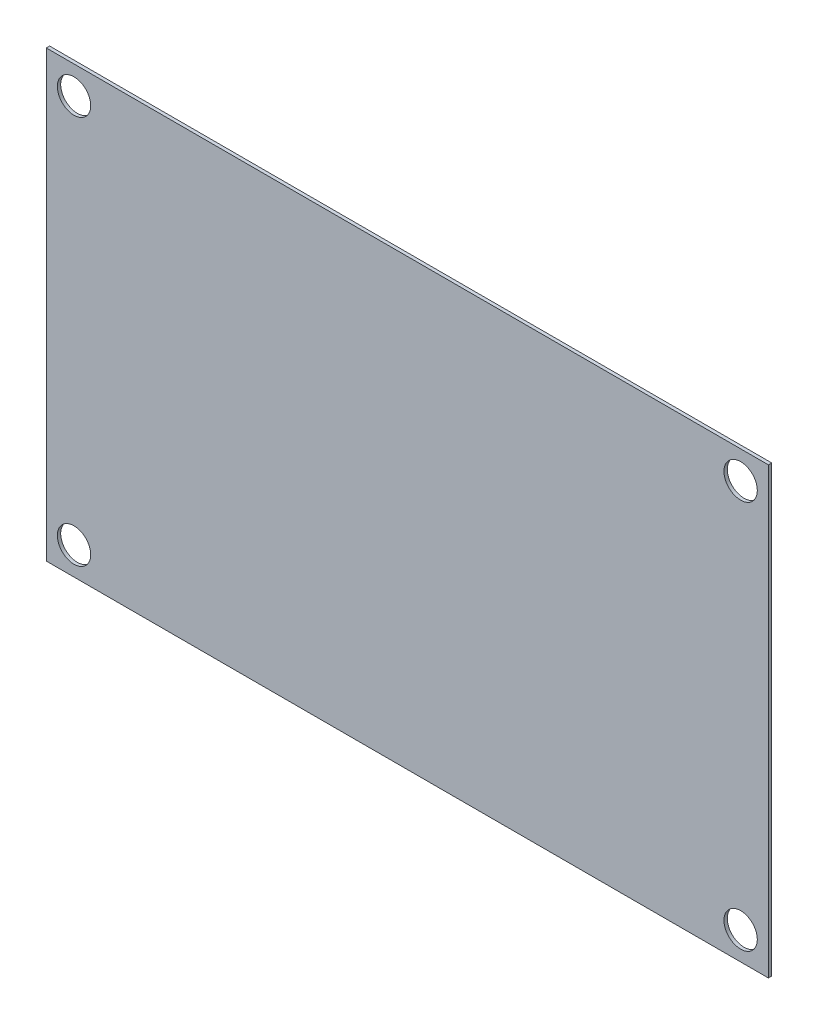
SolidWorks part; units mm, degrees
material "Copper"
ref_plane "Front Plane" through (0, 0, 0) normal (0, 0, 1) x (1, 0, 0)
ref_plane "Top Plane" through (0, 0, 0) normal (0, 1, 0) x (1, 0, 0)
ref_plane "Right Plane" through (0, 0, 0) normal (1, 0, 0) x (0, 0, -1)
sketch "Sketch1" plane through (0, 0, 0) normal (0, 0, 1) x (1, 0, 0)
  line L0 (-32.5, 17.5) -> (-30, 17.5) construction
  line L1 (-32.5, 20) -> (32.5, 20)
  line L2 (-32.5, 20) -> (-32.5, -20)
  line L3 (-32.5, -20) -> (32.5, -20)
  line L4 (32.5, 20) -> (32.5, -20)
  line L5 (-32.5, 20) -> (32.5, -20) construction
  line L6 (-32.5, -20) -> (32.5, 20) construction
  line L7 (-30, 17.5) -> (30, 17.5) construction
  line L8 (30, 17.5) -> (32.5, 17.5) construction
  line L9 (-30, 20) -> (-30, 17.5) construction
  line L10 (-30, 17.5) -> (-30, -17.5) construction
  line L11 (-30, -17.5) -> (-30, -20) construction
  circle A0 centre (-30, 17.5) radius 1.5
  circle A1 centre (-30, -17.5) radius 1.5
  circle A2 centre (30, -17.5) radius 1.5
  circle A3 centre (30, 17.5) radius 1.5
  point P0 (0, 0)
  point P17 (0, 0)
  point P19 (0, 0)
  dimension "D1" = 3
  dimension "D2" = 65
  dimension "D3" = 40
  dimension "D4" = 2.5
  dimension "D5" = 2.5
extrude "Boss-Extrude1" add sketch "Sketch1" along normal blind 0.3
